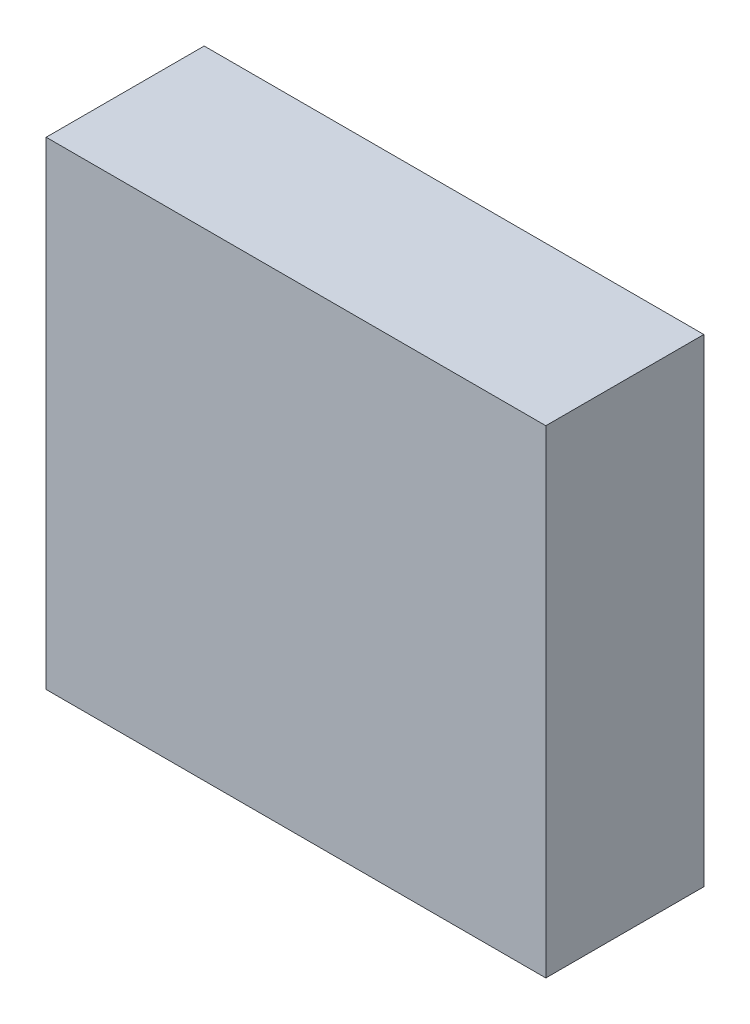
SolidWorks part; units mm, degrees
ref_plane "前视基准面" through (0, 0, 0) normal (0, 0, 1) x (1, 0, 0)
ref_plane "上视基准面" through (0, 0, 0) normal (0, 1, 0) x (1, 0, 0)
ref_plane "右视基准面" through (0, 0, 0) normal (1, 0, 0) x (0, 0, -1)
sketch "草图1" plane through (0, 0, 0) normal (0, 0, 1) x (1, 0, 0)
  line L1 (-58.5, -56) -> (58.5, -56)
  line L2 (-58.5, -56) -> (-58.5, 56)
  line L3 (-58.5, 56) -> (58.5, 56)
  line L4 (58.5, -56) -> (58.5, 56)
  line L5 (-58.5, -56) -> (58.5, 56) construction
  line L6 (-58.5, 56) -> (58.5, -56) construction
  point P0 (0, 0)
  dimension "D1" = 117
  dimension "D2" = 112
extrude "凸台-拉伸1" add sketch "草图1" along normal blind 37 contours L3 L4 L1 L2
